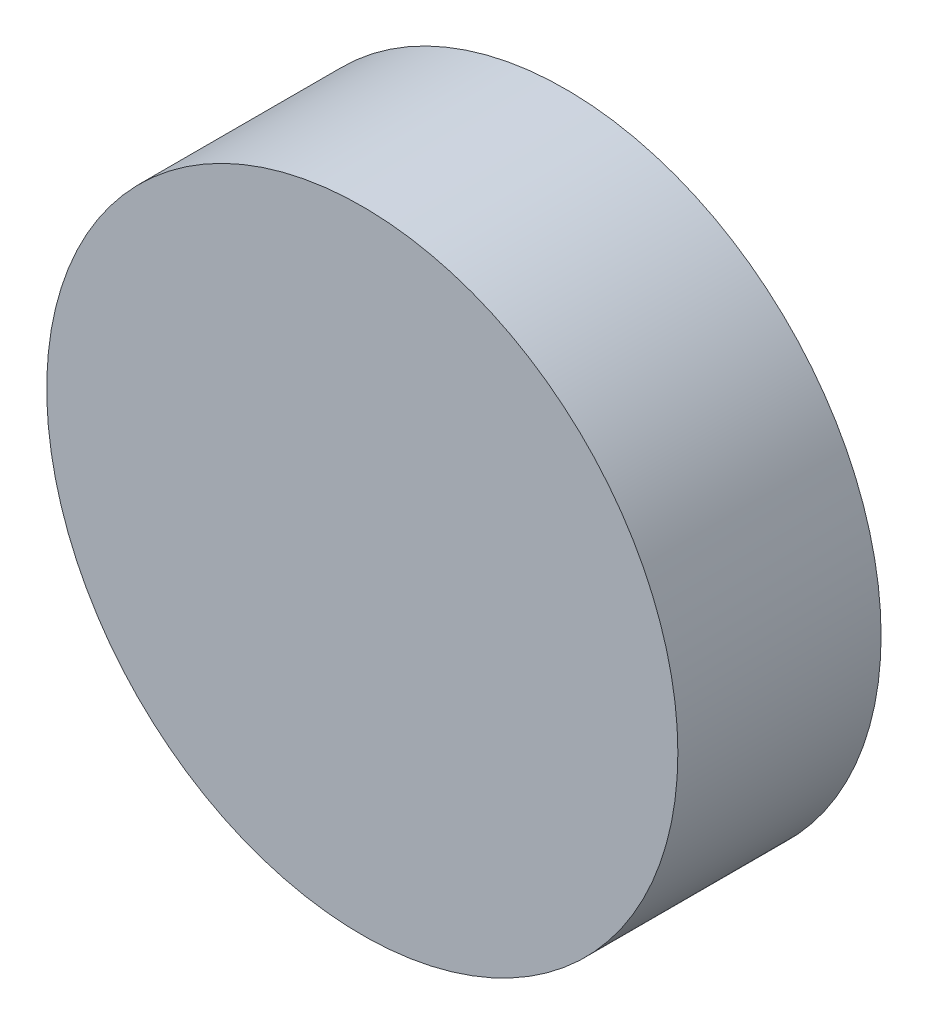
SolidWorks part; units mm, degrees
ref_plane "Front Plane" through (0, 0, 0) normal (0, 0, 1) x (1, 0, 0)
ref_plane "Top Plane" through (0, 0, 0) normal (0, 1, 0) x (1, 0, 0)
ref_plane "Right Plane" through (0, 0, 0) normal (1, 0, 0) x (0, 0, -1)
sketch "Sketch1" plane through (0, 0, 0) normal (0, 0, 1) x (1, 0, 0)
  circle A0 centre (0, 0) radius 63.5
  dimension "D1" = 127
extrude "Boss-Extrude1" add sketch "Sketch1" against normal blind 40.894
